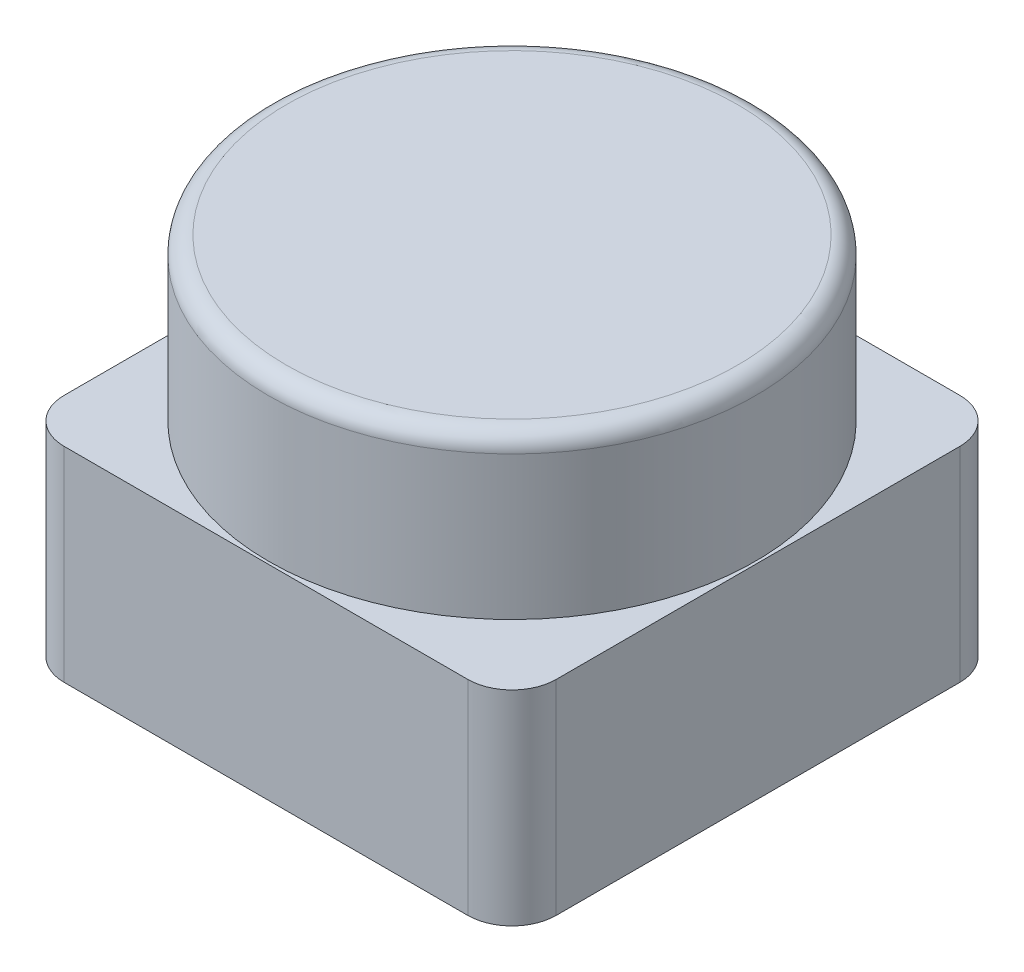
SolidWorks part; units mm, degrees
material "PBT 一般用途"
ref_plane "前视基准面" through (0, 0, 0) normal (0, 0, 1) x (1, 0, 0)
ref_plane "上视基准面" through (0, 0, 0) normal (0, 1, 0) x (1, 0, 0)
ref_plane "右视基准面" through (0, 0, 0) normal (1, 0, 0) x (0, 0, -1)
sketch "草图2" plane through (0, 0, 0) normal (0, 1, 0) x (1, 0, 0)
  line L1 (-27.8, -27.8) -> (27.8, -27.8)
  line L2 (-27.8, -27.8) -> (-27.8, 27.8)
  line L3 (-27.8, 27.8) -> (27.8, 27.8)
  line L4 (27.8, -27.8) -> (27.8, 27.8)
  line L5 (-27.8, -27.8) -> (27.8, 27.8) construction
  line L6 (-27.8, 27.8) -> (27.8, -27.8) construction
  point P0 (0, 0)
  dimension "D1" = 55.6
  dimension "D2" = 55.6
extrude "凸台-拉伸1" add sketch "草图2" along normal blind 23.1
sketch "草图3" plane through (0, 23.1, 0) normal (0, 1, 0) x (1, 0, 0)
  circle A0 centre (0, 0) radius 27.5
  dimension "D1" = 55
extrude "凸台-拉伸2" add sketch "草图3" along normal blind 18.2
sketch "草图4" plane through (0, 0, 0) normal (0, -1, 0) x (1, 0, 0)
  line L1 (-21.5, -21.5) -> (21.5, -21.5)
  line L2 (-21.5, -21.5) -> (-21.5, 21.5)
  line L3 (-21.5, 21.5) -> (21.5, 21.5)
  line L4 (21.5, -21.5) -> (21.5, 21.5)
  line L5 (-21.5, -21.5) -> (21.5, 21.5) construction
  line L6 (-21.5, 21.5) -> (21.5, -21.5) construction
  point P0 (0, 0)
  dimension "D1" = 43
  dimension "D2" = 43
sketch "草图5" plane through (0, 0, 0) normal (0, -1, 0) x (-1, 0, 0)
  point P0 (-21.5, 21.5)
  point P3 (21.5, 21.5)
  point P6 (21.5, -21.5)
  point P9 (-21.5, -21.5)
hole_wizard "孔1" positions "草图5" profile "草图6" legacy
sketch "草图6" plane through (21.5, 0, -21.5) normal (1, 0, 0) x (0, 0, -1)
  line L0 (0, 0) -> (0, 4)
  line L1 (0, 4) -> (1.25, 4)
  line L2 (1.25, 4) -> (1.25, 0)
  line L3 (1.25, 0) -> (0, 0)
  line L4 (0, 110) -> (0, -10) construction
  dimension "直径" = 2.5
  dimension "深度" = 4
fillet "圆角1" radius 5 4 edges at (27.8, 11.55, 27.8) (-27.8, 11.55, 27.8) (-27.8, 11.55, -27.8) (27.8, 11.55, -27.8)
fillet "圆角2" radius 2 1 edges at (0, 41.3, 27.5)
